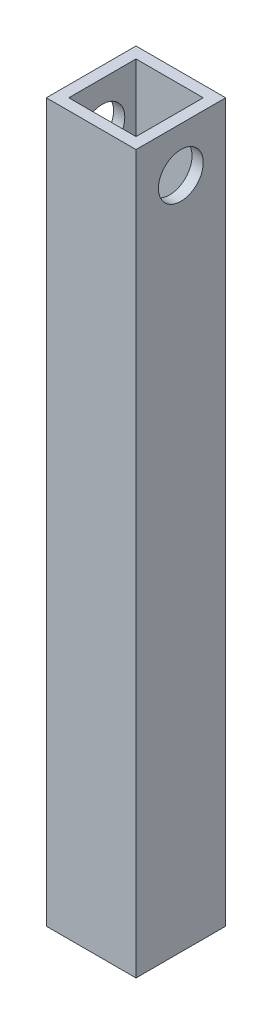
SolidWorks part; units mm, degrees
material "1060 Alloy"
ref_plane "Front Plane" through (0, 0, 0) normal (0, 0, 1) x (1, 0, 0)
ref_plane "Top Plane" through (0, 0, 0) normal (0, 1, 0) x (1, 0, 0)
ref_plane "Right Plane" through (0, 0, 0) normal (1, 0, 0) x (0, 0, -1)
sketch "Sketch1" plane through (0, 0, 0) normal (0, 1, 0) x (1, 0, 0)
  line L1 (-12.7, -12.7) -> (12.7, -12.7)
  line L2 (-12.7, -12.7) -> (-12.7, 12.7)
  line L3 (-12.7, 12.7) -> (12.7, 12.7)
  line L4 (12.7, -12.7) -> (12.7, 12.7)
  line L5 (-12.7, -12.7) -> (12.7, 12.7) construction
  line L6 (-12.7, 12.7) -> (12.7, -12.7) construction
  point P0 (0, 0)
  dimension "D1" = 25.4
extrude "Extrude-Thin1" add sketch "Sketch1" along normal blind 203.2 thin thin type one direction reverse wall 3.175
sketch "Sketch2" plane through (12.7, 0, 0) normal (1, 0, 0) x (0, 0, -1)
  line L0 (-12.7, 203.2) -> (12.7, 203.2) construction
  circle A0 centre (0, 190.5) radius 6.35
  point P5 (0, 203.2)
  dimension "D1" = 12.7
  dimension "D2" = 12.7
extrude "Cut-Extrude1" cut sketch "Sketch2" against normal through all
sketch "Sketch3" [suppressed] plane through (0, 0, -12.7) normal (0, 0, -1) x (-1, 0, 0)
  line L0 (-12.7, 0) -> (12.7, 0) construction
  circle A0 centre (0, 12.7) radius 6.35
  dimension "D1" = 12.7
  dimension "D2" = 12.7
extrude "Cut-Extrude2" [suppressed] cut sketch "Sketch3" against normal through all
